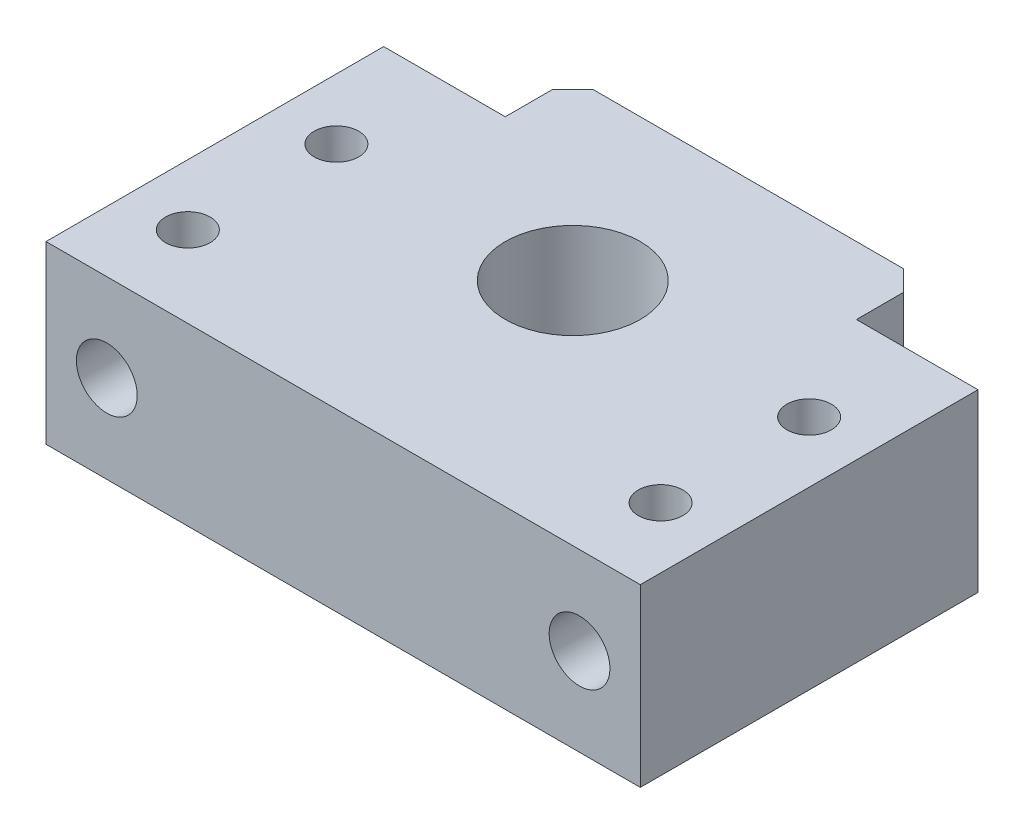
SolidWorks part; units mm, degrees
material "合金钢"
ref_plane "前视基准面" through (0, 0, 0) normal (0, 0, 1) x (1, 0, 0)
ref_plane "上视基准面" through (0, 0, 0) normal (0, 1, 0) x (1, 0, 0)
ref_plane "右视基准面" through (0, 0, 0) normal (1, 0, 0) x (0, 0, -1)
sketch "草图1" plane through (0, 0, 0) normal (0, 1, 0) x (1, 0, 0)
  line L0 (0, 35) -> (0, -25) construction
  line L1 (-44, 25) -> (-26, 25)
  line L2 (-44, 25) -> (-44, -25)
  line L3 (-44, -25) -> (44, -25)
  line L4 (44, 25) -> (44, -25)
  line L5 (-44, 25) -> (-44, -25)
  line L6 (44, 25) -> (44, -25)
  line L7 (26, 25) -> (44, 25)
  line L8 (-26, 35) -> (26, 35)
  line L9 (-26, 35) -> (-26, 25)
  line L11 (26, 35) -> (26, 25)
  circle A0 centre (35, 9) radius 3.3
  circle A1 centre (35, -13) radius 3.3
  circle A2 centre (-35, -13) radius 3.3
  circle A3 centre (-35, 9) radius 3.3
  circle A4 centre (0, 9) radius 10
  point P6 (44, 0)
  point P17 (0, 35)
  dimension "D3" = 6.6
  dimension "D9" = 20
  dimension "D1" = 88
  dimension "D2" = 50
  dimension "D4" = 34
  dimension "D5" = 22
  dimension "D6" = 70
  dimension "D7" = 60
  dimension "D8" = 52
extrude "凸台-拉伸1" add sketch "草图1" along normal blind 26 contours L0 L8 L9 L1 L2 L3 A4 A2 A3 | L8 L0 A4 L3 L4 L7 L11 A0 A1
chamfer "倒角1" distance 3 angle 45 2 edges at (26, 13, -35) (-26, 13, -35)
sketch "草图2" plane through (0, 0, -25) normal (0, 0, -1) x (-1, 0, 0)
  line L0 (0, 26) -> (0, 0) construction
  line L1 (23, 26) -> (-23, 26) construction
  line L2 (-44, 26) -> (-44, 0) construction
  circle A0 centre (-35, 13) radius 7
  circle A1 centre (35, 13) radius 7
  point P12 (-44, 13)
  dimension "D1" = 14
  dimension "D2" = 70
extrude "切除-拉伸1" cut sketch "草图2" against normal blind 12
sketch "草图3" plane through (0, 0, -13) normal (0, 0, -1) x (-1, 0, 0)
  circle A0 centre (-35, 13) radius 4.5
  circle A1 centre (35, 13) radius 4.5
  dimension "D1" = 9
extrude "切除-拉伸2" cut sketch "草图3" against normal through all
